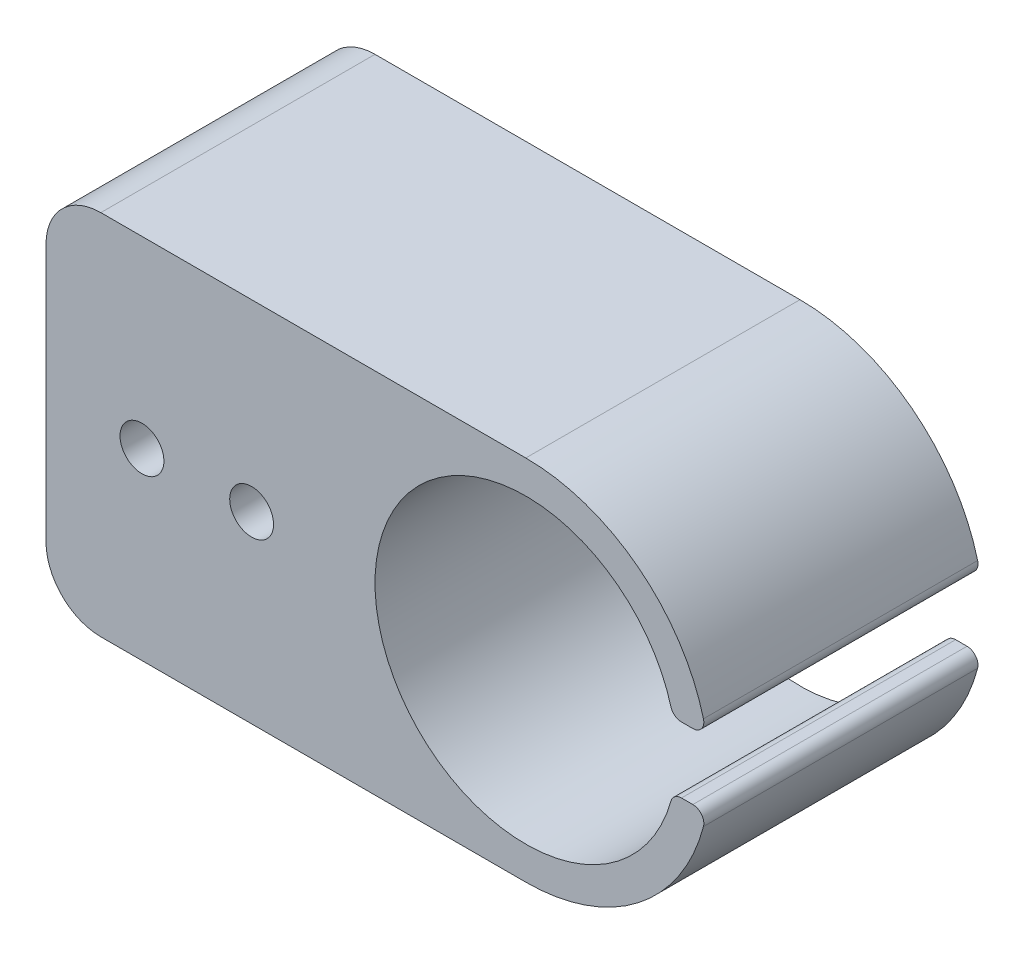
SolidWorks part; units mm, degrees
ref_plane "Plan de face" through (0, 0, 0) normal (0, 0, 1) x (1, 0, 0)
ref_plane "Plan de dessus" through (0, 0, 0) normal (0, 1, 0) x (1, 0, 0)
ref_plane "Plan de droite" through (0, 0, 0) normal (1, 0, 0) x (0, 0, -1)
sketch "Esquisse1" plane through (0, 0, 0) normal (0, 0, 1) x (1, 0, 0)
  line L0 (0, 0) -> (13.75, 0) construction
  line L1 (0, 3) -> (21.7672, 3) construction
  line L2 (0, -3) -> (21.7672, -3) construction
  line L3 (13.4187, 3) -> (16.4792, 3)
  line L4 (16.4792, -3) -> (13.4187, -3)
  line L5 (0, 0) -> (0, 16.75) construction
  line L6 (0, -16.75) -> (-43.75, -16.75)
  line L7 (-43.75, -16.75) -> (-43.75, 16.75)
  line L8 (-43.75, 16.75) -> (0, 16.75)
  circle A0 centre (0, 0) radius 13.75 construction
  arc A1 (13.4187, 3) -> (13.4187, -3) centre (0, 0) ccw
  arc A3 (16.4792, 3) -> (0, 16.75) centre (0, 0) ccw
  arc A4 (16.4792, -3) -> (0, -16.75) centre (0, 0) cw
  circle A5 centre (-35, 0) radius 2
  circle A6 centre (-25, 0) radius 2
  point P18 (-13.75, 0)
  dimension "D1" = 27.5
  dimension "D2" = 6
  dimension "D3" = 30
  dimension "D4" = 3
  dimension "D6" = 4
  dimension "D5" = 10
  dimension "D7" = 25
extrude "Boss.-Extru.1" add sketch "Esquisse1" along normal blind 25
fillet "Congé1" radius 5 2 edges at (-43.75, -16.75, 12.5) (-43.75, 16.75, 12.5)
fillet "Congé2" radius 1 4 edges at (16.4792, -3, 12.5) (16.4792, 3, 12.5) (13.4187, -3, 12.5) (13.4187, 3, 12.5)
sketch "Esquisse2" plane through (0, 0, 0) normal (0, 0, -1) x (-1, 0, 0)
  line L0 (43.75, 10.1) -> (25, 10.1)
  line L1 (43.75, 11.75) -> (43.75, -11.75) construction
  line L2 (25, -10.1) -> (43.75, -10.1)
  line L3 (43.75, -10.1) -> (43.75, 10.1)
  arc A0 (25, 10.1) -> (25, -10.1) centre (25, 0) ccw
  circle A1 centre (25, 0) radius 2 construction
  dimension "D1" = 20.2
extrude "Enlèv. mat.-Extru.1" cut sketch "Esquisse2" against normal blind 10
